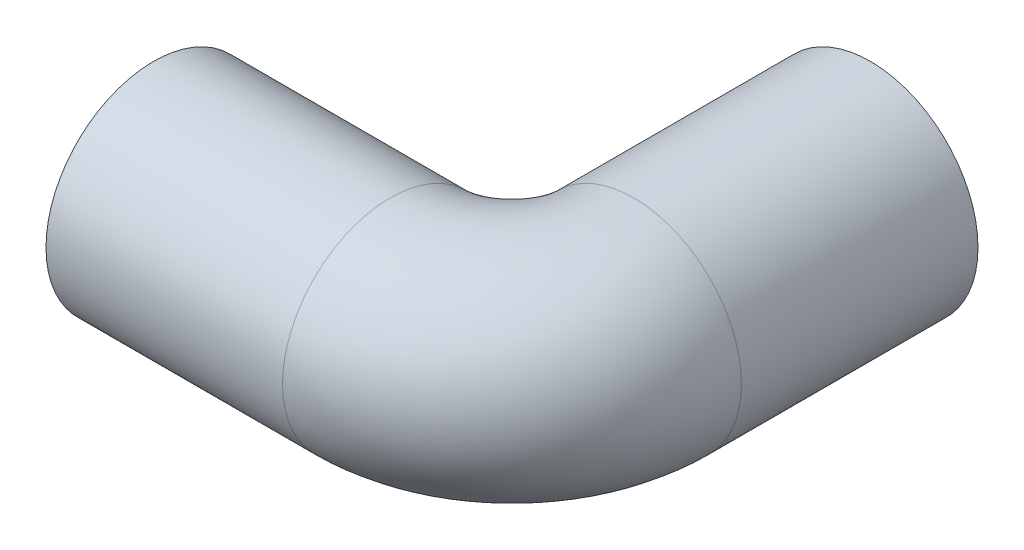
SolidWorks part; units mm, degrees
ref_plane "Front Plane" through (0, 0, 0) normal (0, 0, 1) x (1, 0, 0)
ref_plane "Top Plane" through (0, 0, 0) normal (0, 1, 0) x (1, 0, 0)
ref_plane "Right Plane" through (0, 0, 0) normal (1, 0, 0) x (0, 0, -1)
sketch "Sketch1" plane through (0, 0, 0) normal (0, 1, 0) x (1, 0, 0)
  line L0 (-17, 0) -> (-50, 0)
  line L1 (0, 17) -> (0, 50)
  arc A0 (-17, 0) -> (0, 17) centre (-17, 17) ccw
  point P6 (0, 0)
  dimension "D3" = 17
  dimension "D1" = 50
  dimension "D2" = 50
sweep "Sweep1" add path "Sketch1" circular profile diameter 30 parameters "D3"=30
shell "Shell1" thickness 2
